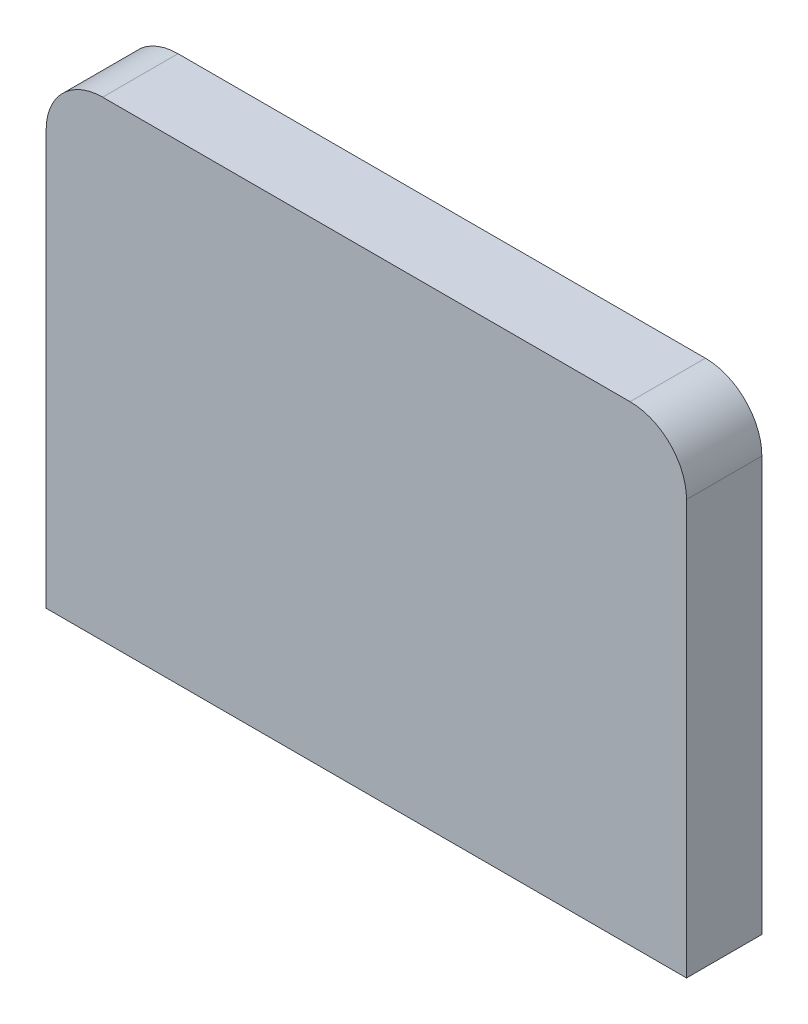
SolidWorks part; units mm, degrees
material "Silicon"
ref_plane "Front Plane" through (0, 0, 0) normal (0, 0, 1) x (1, 0, 0)
ref_plane "Top Plane" through (0, 0, 0) normal (0, 1, 0) x (1, 0, 0)
ref_plane "Right Plane" through (0, 0, 0) normal (1, 0, 0) x (0, 0, -1)
sketch "Sketch1" plane through (0, 0, 0) normal (0, 0, 1) x (1, 0, 0)
  line L1 (-50.6339, 31.5503) -> (-7.4539, 31.5503)
  line L2 (-50.6339, 31.5503) -> (-50.6339, -0.1997)
  line L3 (-50.6339, -0.1997) -> (-7.4539, -0.1997)
  line L4 (-7.4539, 31.5503) -> (-7.4539, -0.1997)
  dimension "D1" = 43.18
  dimension "D2" = 31.75
extrude "Boss-Extrude1" add sketch "Sketch1" along normal blind 5.08
fillet "Fillet1" radius 3.81 2 edges at (-7.4539, 31.5503, 2.54) (-50.6339, 31.5503, 2.54)
